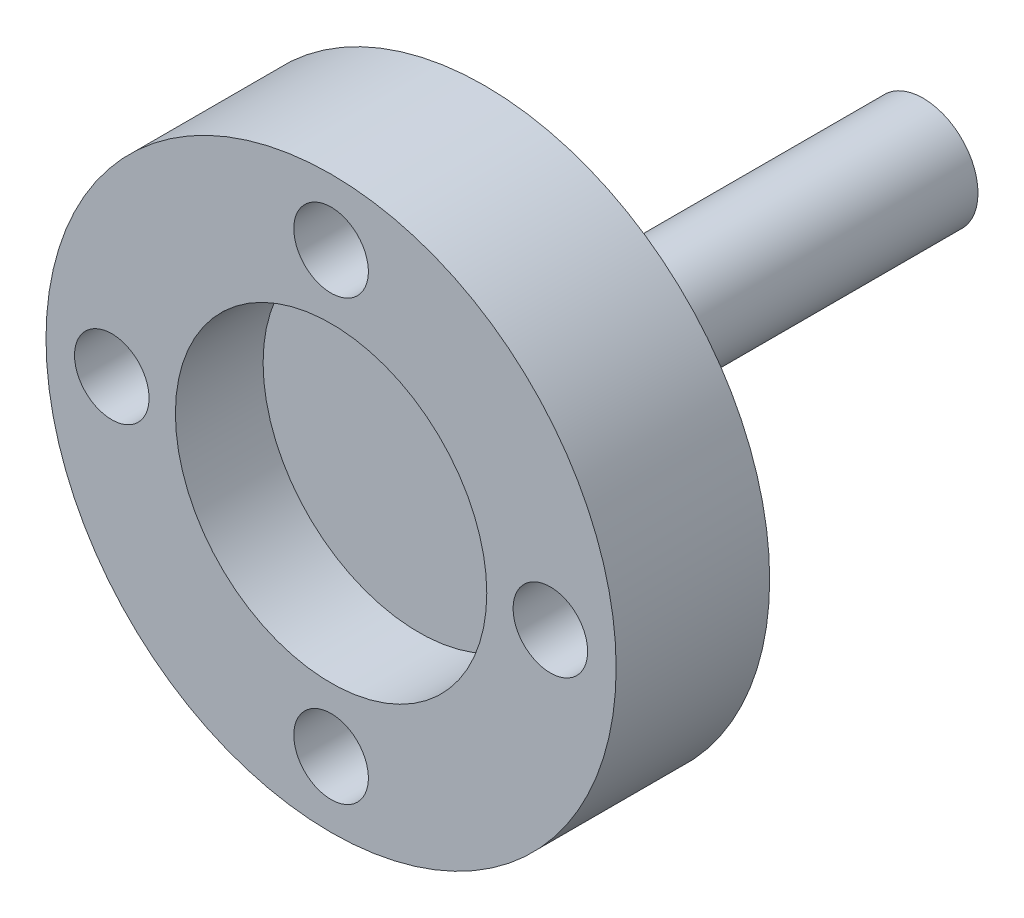
SolidWorks part; units mm, degrees
ref_plane "Спереди" through (0, 0, 0) normal (0, 0, 1) x (1, 0, 0)
ref_plane "Сверху" through (0, 0, 0) normal (0, 1, 0) x (1, 0, 0)
ref_plane "Справа" through (0, 0, 0) normal (1, 0, 0) x (0, 0, -1)
sketch "Эскиз1" plane through (0, 0, 0) normal (0, 0, 1) x (1, 0, 0)
  circle A0 centre (0, 0) radius 13
  dimension "D1" = 26
extrude "Бобышка-Вытянуть1" add sketch "Эскиз1" along normal blind 7
sketch "Эскиз2" plane through (0, 0, 7) normal (0, 0, 1) x (1, 0, 0)
  circle A0 centre (0, 0) radius 7.1
  dimension "D1" = 14.2
extrude "Вырез-Вытянуть1" cut sketch "Эскиз2" against normal blind 4
sketch "Эскиз3" plane through (0, 0, 0) normal (0, 0, -1) x (-1, 0, 0)
  circle A0 centre (0, 0) radius 2.5
  dimension "D1" = 5
extrude "Бобышка-Вытянуть2" add sketch "Эскиз3" along normal blind 20
sketch "Эскиз4" plane through (0, 0, 0) normal (0, 0, -1) x (-1, 0, 0)
  line L0 (0, 13) -> (0, -13) construction
  line L1 (13, 0) -> (-13, 0) construction
  circle A0 centre (0, 0) radius 10 construction
  circle A1 centre (0, 0) radius 13 construction
  dimension "D1" = 20
hole_wizard "Отверстие с зазором M31" positions "Эскиз6" profile "Эскиз5" hole size "M3" standard "Ansi Metric" end condition through all
sketch "Эскиз6" plane through (0, 0, 0) normal (0, 0, -1) x (-1, 0, 0)
  line L0 (0, 13) -> (0, -13) construction
  line L1 (13, 0) -> (-13, 0) construction
  circle A0 centre (0, 0) radius 10 construction
  point P0 (0, 10)
  point P6 (-10, 0)
  point P10 (0, -10)
  point P12 (10, 0)
sketch "Эскиз5" plane through (0, 10, 0) normal (1, 0, 0) x (0, 1, 0)
  line L0 (0, 0) -> (0, 7)
  line L1 (0, 7) -> (1.7, 7)
  line L2 (1.7, 7) -> (1.7, 0)
  line L5 (1.7, 0) -> (0, 0)
  line L11 (0, -6.35) -> (0, 107.95) construction
  dimension "Диаметр сквозного отверстия" = 3.4
  dimension "Глубина сквозного отверстия" = 7
